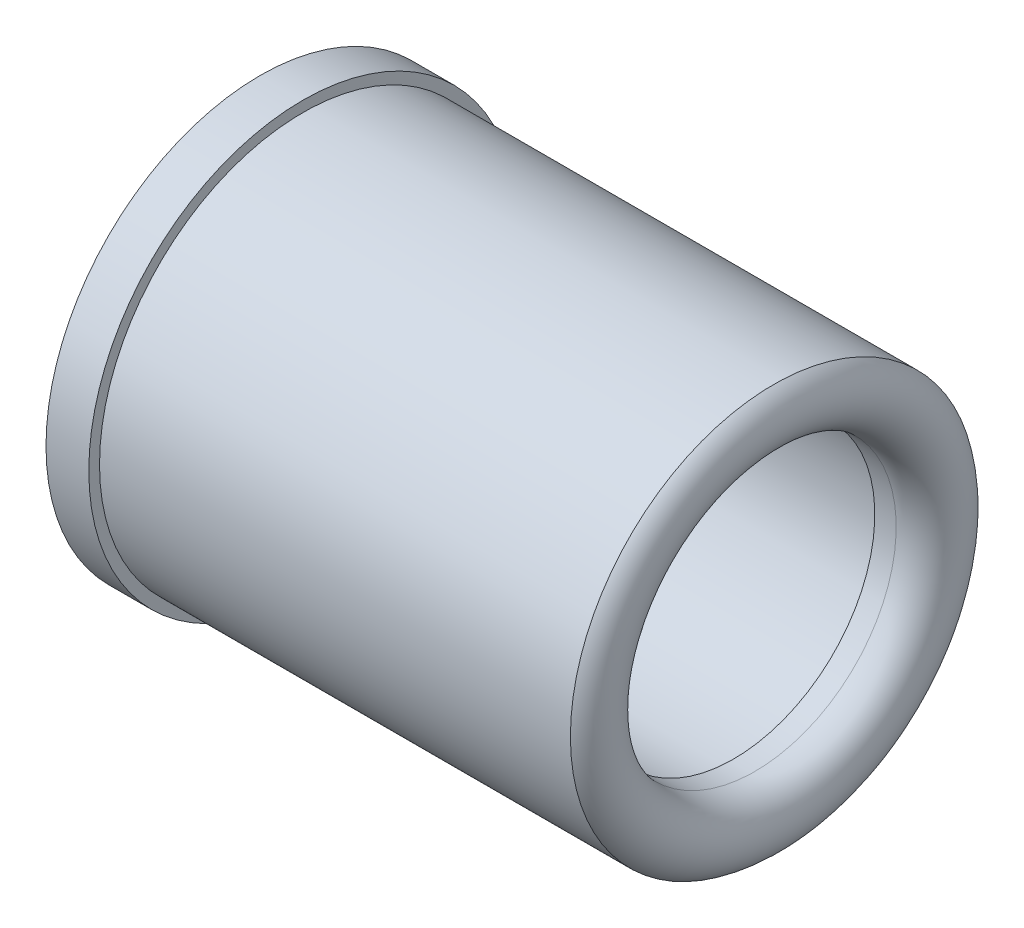
SolidWorks part; units mm, degrees
ref_plane "Front Plane" through (0, 0, 0) normal (0, 0, 1) x (1, 0, 0)
ref_plane "Top Plane" through (0, 0, 0) normal (0, 1, 0) x (1, 0, 0)
ref_plane "Right Plane" through (0, 0, 0) normal (1, 0, 0) x (0, 0, -1)
ref_plane "Plane1" through (0, 0, 0) normal (0, 0, -1) x (-1, 0, 0)
sketch "Sketch1" plane through (0, 0, 0) normal (0, 0, -1) x (-1, 0, 0)
  line L0 (-11.9728, -5.2333) -> (-11.9728, -4.9833)
  line L1 (-11.9728, -4.9833) -> (-0.9121, -4.9833)
  line L2 (-0.9121, -4.9833) -> (-0.9121, -3.5333)
  line L3 (-0.9121, -3.5333) -> (-1.9121, -3.5333)
  line L4 (-1.9121, -3.5333) -> (-1.9121, -3.7833)
  line L5 (-1.9121, -3.7833) -> (-12.9121, -3.7833)
  line L6 (-12.4728, -5.2333) -> (-11.9728, -5.2333)
  line L7 (-12.1757, -8.5333) -> (0.2029, -8.5333) construction
  arc A0 (-12.9121, -3.7833) -> (-12.4728, -5.2333) centre (-12.4728, -4.4417) ccw
  dimension "D1" = 11
  dimension "D2" = 10
  dimension "D3" = 0.25
  dimension "D4" = 0.25
  dimension "D5" = 1.45
  dimension "D6" = 1
  dimension "D7" = 0.5
revolve "Revolve1" add sketch "Sketch1" angle 360 about L7
